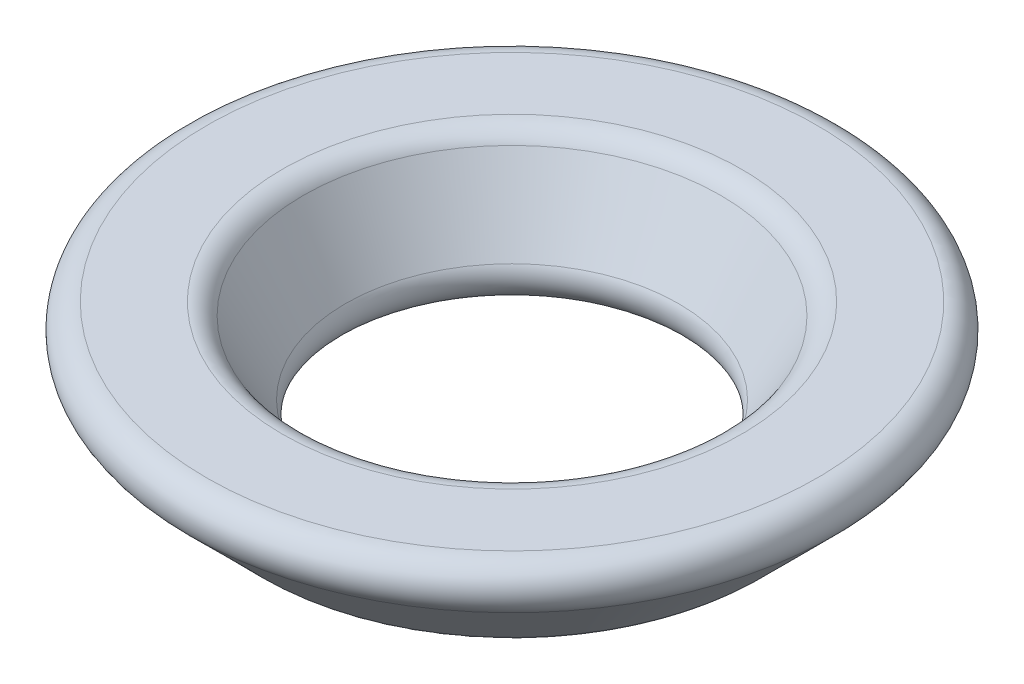
SolidWorks part; units mm, degrees
ref_plane "Front Plane" through (0, 0, 0) normal (0, 0, 1) x (1, 0, 0)
ref_plane "Top Plane" through (0, 0, 0) normal (0, 1, 0) x (1, 0, 0)
ref_plane "Right Plane" through (0, 0, 0) normal (1, 0, 0) x (0, 0, -1)
sketch "Sketch1" plane through (0, 0, 0) normal (0, 0, 1) x (1, 0, 0)
  line L0 (-12.7, 0) -> (-19.05, 6.35)
  line L1 (-19.05, 6.35) -> (-11.2862, 6.35)
  line L2 (-11.2862, 6.35) -> (-7.62, 0)
  line L3 (-7.62, 0) -> (-12.7, 0)
  dimension "D1" = 12.7
  dimension "D2" = 45
  dimension "D3" = 6.35
  dimension "D4" = 60
  dimension "D5" = 5.08
ref_axis "Axis1" through (0, 6.6675, 0) along (0, -1, 0)
revolve "Revolve1" add sketch "Sketch1" angle 360 about axis through (0, 6.6675, 0) along (0, -1, 0)
fillet "Fillet1" radius 1.27 4 edges at (0, 0, 12.7) (0, 6.35, 19.05) (0, 0, 7.62) (0, 6.35, 11.2862)
